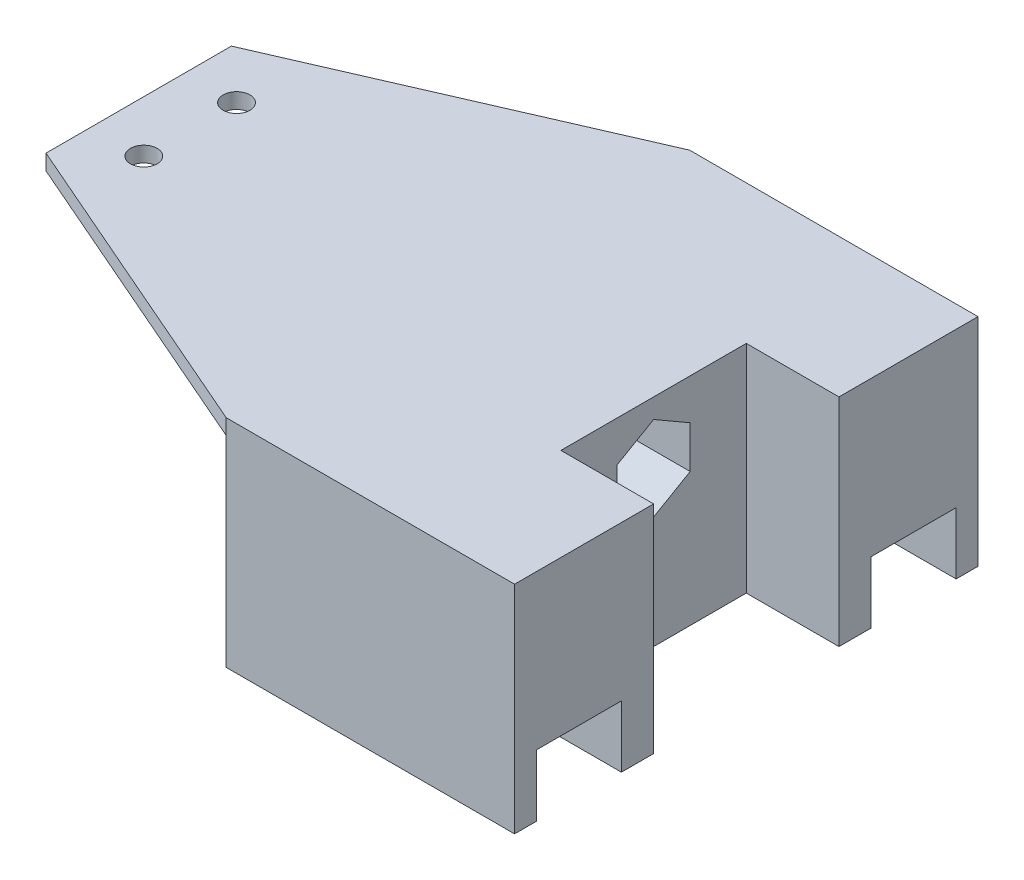
SolidWorks part; units mm, degrees
ref_plane "Front Plane" through (0, 0, 0) normal (0, 0, 1) x (1, 0, 0)
ref_plane "Top Plane" through (0, 0, 0) normal (0, 1, 0) x (1, 0, 0)
ref_plane "Right Plane" through (0, 0, 0) normal (1, 0, 0) x (0, 0, -1)
sketch "Sketch1" plane through (0, 0, 0) normal (1, 0, 0) x (0, 0, -1)
  line L0 (0, 52.2301) -> (0, 21) construction
  line L1 (-22.5, 0) -> (-22.5, 21)
  line L2 (-22.5, 21) -> (22.5, 21)
  line L10 (-20.375, 0) -> (-22.5, 0)
  line L11 (0, 15) -> (0, -0.8537) construction
  line L13 (0, 10.9008) -> (3.55, 12.9504)
  line L14 (3.55, 12.9504) -> (3.55, 17.0496)
  line L15 (3.55, 17.0496) -> (0, 19.0992)
  line L16 (0, 19.0992) -> (-3.55, 17.0496)
  line L17 (-3.55, 17.0496) -> (-3.55, 12.9504)
  line L18 (-3.55, 12.9504) -> (0, 10.9008)
  line L23 (22.5, 0) -> (22.5, 21)
  line L24 (20.375, 0) -> (22.5, 0)
  line L26 (0, 0) -> (0, -37.6322) construction
  line L32 (-12.125, 0) -> (12.125, 0)
  line L34 (-20.375, 0) -> (-20.375, 6)
  line L35 (-20.375, 6) -> (-12.125, 6)
  line L36 (-12.125, 0) -> (-12.125, 6)
  line L37 (-16.25, 6) -> (-16.25, 0.0816) construction
  line L41 (12.125, 0) -> (12.125, 6)
  line L42 (20.375, 6) -> (12.125, 6)
  line L43 (20.375, 0) -> (20.375, 6)
  circle A3 centre (0, 15) radius 3.55 construction
  dimension "D1" = 7.1
  dimension "D3" = 8.1984
  dimension "D5" = 8.25
  dimension "D4" = 15
  dimension "D7" = 21
  dimension "D2" = 22.5
  dimension "D6" = 6
  dimension "D8" = 16.25
extrude "Boss-Extrude1" add sketch "Sketch1" along normal mid plane 28
sketch "Sketch2" plane through (0, 21, 0) normal (0, 1, 0) x (1, 0, 0)
  line L5 (-14, 22.5) -> (-14, -22.5) construction
  line L6 (-23, 9) -> (-5, 9)
  line L7 (0, 22.5) -> (0, -22.5) construction
  line L8 (14, 22.5) -> (-14, 22.5) construction
  line L9 (14, -22.5) -> (-14, -22.5) construction
  line L14 (-23, 9) -> (-23, -9)
  line L15 (-23, -9) -> (-5, -9)
  line L16 (-5, 9) -> (-5, -9)
  line L17 (-23, 9) -> (-5, -9) construction
  line L18 (-23, -9) -> (-5, 9) construction
  line L19 (14, 22.5) -> (14, -22.5) construction
  line L20 (5, 9) -> (23, 9)
  line L21 (5, 9) -> (5, -9)
  line L22 (5, -9) -> (23, -9)
  line L23 (23, 9) -> (23, -9)
  line L24 (5, 9) -> (23, -9) construction
  line L25 (5, -9) -> (23, 9) construction
  point P0 (-14, 0)
  point P7 (14, 0)
  dimension "D1" = 18
  dimension "D2" = 18
  dimension "D3" = 18
  dimension "D4" = 18
  dimension "D5" = 5
  dimension "D6" = 5
extrude "Cut-Extrude1" cut sketch "Sketch2" against normal up to surface (21 mm away) up to face at (0, 0, 0)
sketch "Sketch3" plane through (0, 21, 0) normal (0, 1, 0) x (1, 0, 0)
  line L0 (-45, 0) -> (-39.8244, 0) construction
  line L2 (-5, -9) -> (-5, 9)
  line L4 (-45, -9) -> (-45, 9)
  line L5 (-5, -9) -> (-5, 9) construction
  line L6 (-14, -22.5) -> (-45, -9)
  line L7 (-45, 9) -> (-14, 22.5)
  line L8 (-5, 9) -> (-14, 22.5)
  line L9 (-14, -22.5) -> (-5, -9)
  circle A0 centre (-40, 4.5) radius 1.3
  circle A1 centre (-40, -4.5) radius 1.3
  point P6 (-5, 0)
  dimension "D5" = 2.6
  dimension "D1" = 40
  dimension "D2" = 18
  dimension "D3" = 18
  dimension "D4" = 9
  dimension "D6" = 5
extrude "Boss-Extrude2" add sketch "Sketch3" against normal blind 1.5
